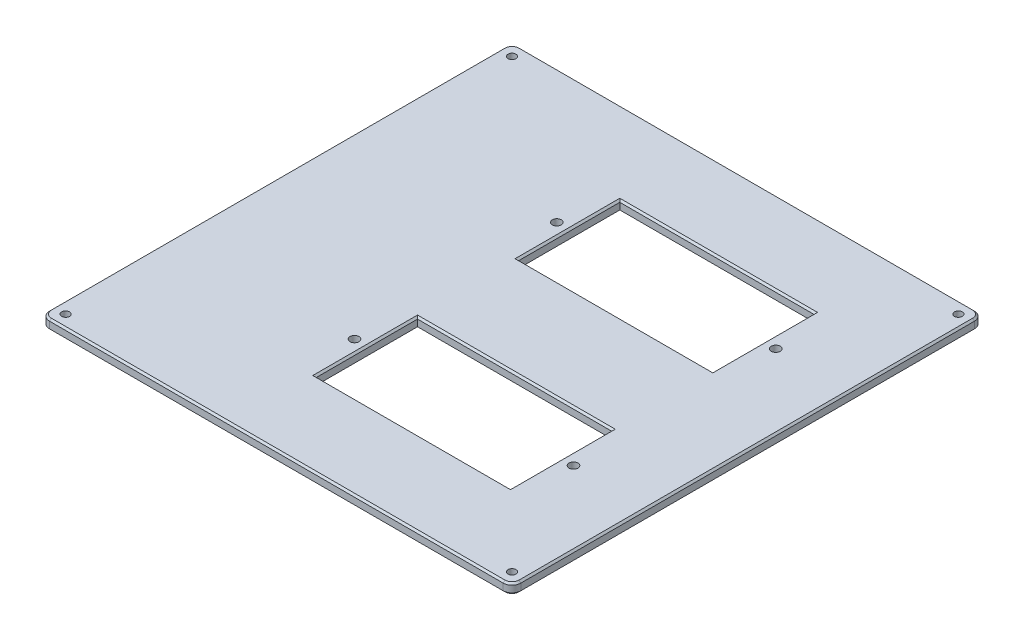
SolidWorks part; units mm, degrees
ref_plane "Front Plane" through (0, 0, 0) normal (0, 0, 1) x (1, 0, 0)
ref_plane "Top Plane" through (0, 0, 0) normal (0, 1, 0) x (1, 0, 0)
ref_plane "Right Plane" through (0, 0, 0) normal (1, 0, 0) x (0, 0, -1)
sketch "Sketch1" plane through (0, 0, 0) normal (0, 1, 0) x (1, 0, 0)
  line L1 (-134.145, 134.145) -> (134.145, 134.145)
  line L2 (-134.145, 134.145) -> (-134.145, -134.145)
  line L3 (-134.145, -134.145) -> (134.145, -134.145)
  line L4 (134.145, 134.145) -> (134.145, -134.145)
  line L5 (-134.145, 134.145) -> (134.145, -134.145) construction
  line L6 (-134.145, -134.145) -> (134.145, 134.145) construction
  line L7 (85.145, 86.845) -> (-25.455, 86.845)
  line L8 (85.145, 86.845) -> (85.145, 29.195)
  line L9 (85.145, 29.195) -> (-25.455, 29.195)
  line L10 (-25.455, 86.845) -> (-25.455, 29.195)
  line L11 (85.145, -28.345) -> (-25.455, -28.345)
  line L12 (85.145, -28.345) -> (85.145, -85.995)
  line L13 (85.145, -85.995) -> (-25.455, -85.995)
  line L14 (-25.455, -28.345) -> (-25.455, -85.995)
  circle A0 centre (-127.095, 127.095) radius 2.25
  circle A1 centre (127.095, 127.095) radius 2.25
  circle A2 centre (127.095, -127.095) radius 2.25
  circle A3 centre (-127.095, -127.095) radius 2.25
  circle A4 centre (-32.505, 58.02) radius 2.55
  circle A5 centre (-32.505, -57.17) radius 2.55
  circle A6 centre (92.195, -57.17) radius 2.55
  circle A7 centre (92.195, 58.02) radius 2.55
  point P0 (0, 0)
  point P37 (85.145, -57.17)
  point P39 (85.145, 58.02)
  dimension "D2" = 4.5
  dimension "D3" = 7.05
  dimension "D9" = 5.1
  dimension "D1" = 268.29
  dimension "D4" = 47.3
  dimension "D5" = 57.65
  dimension "D6" = 48.15
  dimension "D7" = 110.6
  dimension "D8" = 49
  dimension "D10" = 7.05
  dimension "D11" = 7.05
extrude "Boss-Extrude1" add sketch "Sketch1" along normal blind 5.8
fillet "Fillet1" radius 5 4 edges at (134.145, 2.9, 134.145) (134.145, 2.9, -134.145) (-134.145, 2.9, -134.145) (-134.145, 2.9, 134.145)
chamfer "Chamfer1" distance 1 angle 45 32 edges at (85.145, 0, -58.02) (29.845, 0, -86.845) (29.845, 0, -29.195) (-25.455, 0, -58.02) (-134.145, 0, 0) (0, 0, -134.145) (0, 0, 134.145) (134.145, 0, 0) (85.145, 5.8, -58.02) (29.845, 5.8, -29.195) (-25.455, 5.8, -58.02) (29.845, 5.8, -86.845) (0, 5.8, -134.145) (-134.145, 5.8, 0) (0, 5.8, 134.145) (134.145, 5.8, 0) (-25.455, 0, 57.17) (29.845, 0, 85.995) (85.145, 0, 57.17) (29.845, 0, 28.345) (85.145, 5.8, 57.17) (29.845, 5.8, 85.995) (-25.455, 5.8, 57.17) (29.845, 5.8, 28.345) (-132.6805, 0, 132.6805) (-132.6805, 0, -132.6805) (132.6805, 0, 132.6805) (132.6805, 0, -132.6805) (-132.6805, 5.8, 132.6805) (-132.6805, 5.8, -132.6805) (132.6805, 5.8, 132.6805) (132.6805, 5.8, -132.6805)
